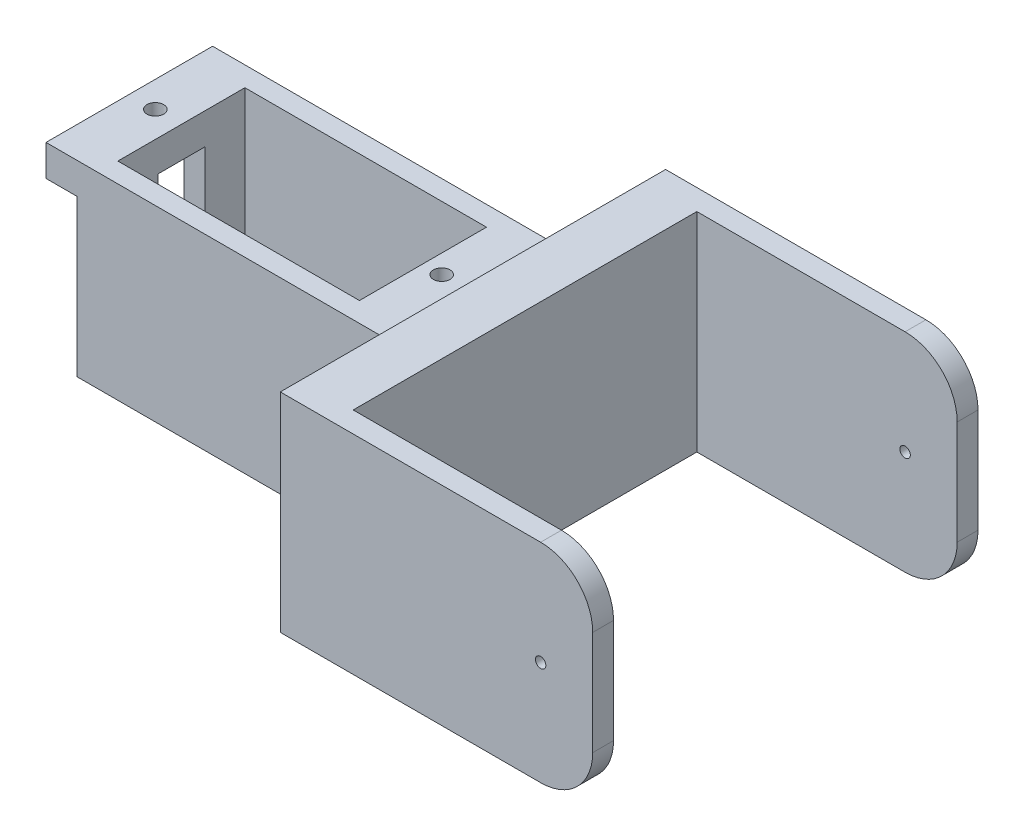
SolidWorks part; units mm, degrees
material "ABS"
ref_plane "Front Plane" through (0, 0, 0) normal (0, 0, 1) x (1, 0, 0)
ref_plane "Top Plane" through (0, 0, 0) normal (0, 1, 0) x (1, 0, 0)
ref_plane "Right Plane" through (0, 0, 0) normal (1, 0, 0) x (0, 0, -1)
sketch "Sketch1" plane through (0, 0, 0) normal (0, 1, 0) x (1, 0, 0)
  line L1 (15, -8) -> (-15, -8)
  line L2 (15, -8) -> (15, 8)
  line L3 (15, 8) -> (-15, 8)
  line L4 (-15, -8) -> (-15, 8)
  line L5 (15, -8) -> (-15, 8) construction
  line L6 (15, 8) -> (-15, -8) construction
  point P0 (0, 0)
  dimension "D1" = 30
  dimension "D2" = 16
extrude "Boss-Extrude1" add sketch "Sketch1" along normal blind 2
sketch "Sketch2" plane through (0, 2, 0) normal (0, 1, 0) x (1, 0, 0)
  line L0 (-1000, 0) -> (49000, 0) construction
  line L1 (-15, -8) -> (15, -8) construction
  line L2 (-15, 8) -> (-13, 8)
  line L3 (-15, 8) -> (-15, -8)
  line L4 (-15, -8) -> (-13, -8)
  line L5 (-13, 6.1) -> (-13, -6.1)
  line L6 (-13, -8) -> (10.2, -8)
  line L7 (-13, 8) -> (10.2, 8)
  line L9 (-13, 6.1) -> (10.2, 6.1)
  line L12 (-13, -6.1) -> (10.2, -6.1)
  line L13 (10.2, 8) -> (15, 8)
  line L14 (10.2, 6.1) -> (10.2, -6.1)
  line L15 (10.2, -8) -> (15, -8)
  line L16 (15, 8) -> (15, -8)
  dimension "D1" = 2
  dimension "D2" = 1.9
  dimension "D3" = 23.2
  dimension "D4" = 4.8
  dimension "D5" = 2
  dimension "D6" = 12.2
extrude "Boss-Extrude2" add sketch "Sketch2" along normal blind 16
sketch "Sketch3" plane through (-13, 0, 0) normal (1, 0, 0) x (0, 0, -1)
  line L0 (0, -1000) -> (0, 49000) construction
  line L1 (8, 0) -> (-8, 0) construction
  line L2 (2.25, 18) -> (-2.25, 18)
  line L3 (2.25, 18) -> (2.25, 5)
  line L4 (2.25, 5) -> (-2.25, 5)
  line L5 (-2.25, 18) -> (-2.25, 5)
  line L6 (2.25, 18) -> (-2.25, 5) construction
  line L7 (2.25, 5) -> (-2.25, 18) construction
  line L8 (8, 18) -> (-8, 18) construction
  point P1 (0, 11.5)
  dimension "D1" = 5
  dimension "D2" = 13
  dimension "D3" = 4.5
extrude "Cut-Extrude1" cut sketch "Sketch3" against normal up to next
sketch "Sketch8" plane through (0, 0, 0) normal (0, -1, 0) x (1, 0, 0)
  line L0 (-1000, 0) -> (49000, 0) construction
  line L1 (-15, -8) -> (-15, 8) construction
  circle A0 centre (-10, 0) radius 0.8
  dimension "D1" = 1.6
  dimension "D2" = 5
extrude "Cut-Extrude3" cut sketch "Sketch8" against normal blind 2
sketch "Sketch9" plane through (0, 18, 0) normal (0, 1, 0) x (1, 0, 0)
  line L0 (15, 8) -> (-15, 8) construction
  line L1 (-13, 8) -> (-18, 8)
  line L2 (-13, 8) -> (-13, -8)
  line L3 (-13, -8) -> (-18, -8)
  line L4 (-18, 8) -> (-18, -8)
  line L5 (-13, 6.1) -> (-13, 2.25) construction
  line L6 (0, -1000) -> (0, 49000) construction
  line L7 (10.2, -6.1) -> (10.2, 6.1) construction
  line L8 (10.2, 8) -> (14.2, 8)
  line L9 (10.2, 8) -> (10.2, -8)
  line L10 (10.2, -8) -> (14.2, -8)
  line L11 (14.2, 8) -> (14.2, -8)
  dimension "D1" = 5
  dimension "D2" = 16
  dimension "D3" = 4
  dimension "D4" = 16
extrude "Boss-Extrude4" add sketch "Sketch9" against normal blind 3
sketch "Sketch10" plane through (0, 18, 0) normal (0, 1, 0) x (1, 0, 0)
  line L0 (-1000, 0) -> (49000, 0) construction
  line L1 (10.2, -6.1) -> (10.2, 6.1) construction
  line L2 (-13, 6.1) -> (-13, -6.1) construction
  circle A0 centre (12, 0) radius 0.8
  circle A1 centre (-15.501, 0) radius 0.8
  dimension "D1" = 1.6
  dimension "D3" = 1.6
  dimension "D2" = 1.8
  dimension "D4" = 2.501
extrude "Cut-Extrude4" cut sketch "Sketch10" against normal blind 5
sketch "Sketch11" plane through (15, 0, 0) normal (1, 0, 0) x (0, 0, -1)
  line L0 (0, -978.5) -> (0, 49021.5) construction
  line L1 (-8, 18) -> (8, 18) construction
  line L2 (-1008, 9) -> (48992, 9) construction
  line L3 (-8, 18) -> (-8, 0) construction
  line L5 (18.5, -1) -> (-18.5, -1)
  line L6 (18.5, -1) -> (18.5, 19)
  line L7 (18.5, 19) -> (-18.5, 19)
  line L8 (-18.5, -1) -> (-18.5, 19)
  line L9 (18.5, -1) -> (-18.5, 19) construction
  line L10 (18.5, 19) -> (-18.5, -1) construction
  point P5 (0, 18)
  point P6 (0, 9)
  point P10 (-8, 9)
  dimension "D1" = 20
  dimension "D2" = 37
extrude "Boss-Extrude5" add sketch "Sketch11" along normal blind 5
sketch "Sketch12" plane through (20, 0, 0) normal (1, 0, 0) x (0, 0, -1)
  line L0 (0, -1000) -> (0, 49000) construction
  line L1 (-1017.5, 9) -> (48982.5, 9) construction
  line L2 (-18.5, 19) -> (-18.5, -1) construction
  line L3 (-18.5, 19) -> (-18.5, -1)
  line L4 (-18.5, 19) -> (-16.5, 19)
  line L5 (-18.5, -1) -> (-16.5, -1)
  line L6 (-16.5, 19) -> (-16.5, -1)
  line L7 (16.5, 19) -> (16.5, -1)
  line L8 (18.5, -1) -> (16.5, -1)
  line L9 (18.5, 19) -> (16.5, 19)
  line L10 (18.5, 19) -> (18.5, -1)
  point P8 (-18.5, 9)
  dimension "D1" = 2
extrude "Boss-Extrude6" add sketch "Sketch12" along normal blind 25
fillet "Fillet1" radius 5 4 edges at (45, 19, 17.5) (45, -1, 17.5) (45, -1, -17.5) (45, 19, -17.5)
sketch "Sketch13" plane through (0, 0, -18.5) normal (0, 0, -1) x (-1, 0, 0)
  line L0 (-1015, 9) -> (48985, 9) construction
  line L1 (-15, -1) -> (-15, 19) construction
  circle A0 centre (-40, 9) radius 0.5
  point P5 (-15, 9)
  dimension "D1" = 1
  dimension "D2" = 25
extrude "Cut-Extrude5" cut sketch "Sketch13" against normal through all both and the other way through all
